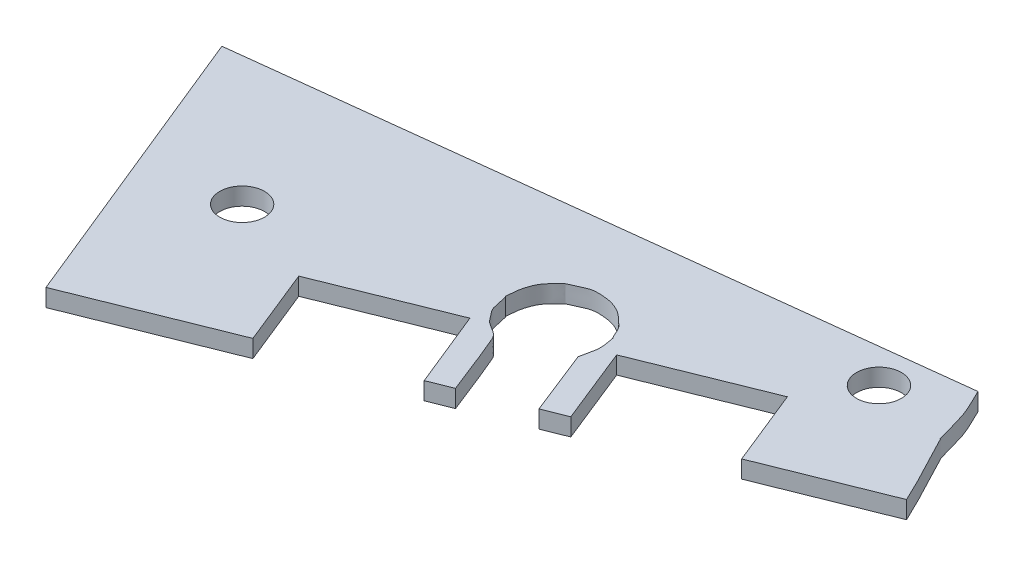
SolidWorks part; units mm, degrees
ref_plane "Front Plane" through (0, 0, 0) normal (0, 0, 1) x (1, 0, 0)
ref_plane "Top Plane" through (0, 0, 0) normal (0, 1, 0) x (1, 0, 0)
ref_plane "Right Plane" through (0, 0, 0) normal (1, 0, 0) x (0, 0, -1)
sketch "Sketch1" plane through (0, 0, 0) normal (0, 1, 0) x (1, 0, 0)
  line L0 (6.1521, 12.0078) -> (30.7603, 12.0078) construction
  line L1 (-3.9482, 25.8578) -> (34.7084, 30.3726)
  line L2 (41.3065, 14.4944) -> (26.3793, 8.5562)
  line L3 (26.3793, 8.5562) -> (21.5711, 20.6728)
  line L4 (22.9999, 7.2071) -> (6.3717, 0.5247)
  line L5 (6.3717, 0.5247) -> (-3.9482, 25.8578)
  line L6 (29.528, 24.668) -> (31.2954, 20.2924)
  line L11 (31.2954, 20.2924) -> (24.3349, 17.4974)
  line L12 (24.3349, 17.4974) -> (22.5827, 21.866)
  line L13 (22.5827, 21.866) -> (29.528, 24.668)
  line L14 (16.5778, 19.4932) -> (18.3623, 15.098)
  line L19 (18.3623, 15.098) -> (11.3765, 12.3133)
  line L20 (11.3765, 12.3133) -> (9.6115, 16.6866)
  line L21 (9.6115, 16.6866) -> (16.5778, 19.4932)
  line L22 (32.7866, 19.2988) -> (34.5598, 14.9094)
  line L23 (34.5598, 14.9094) -> (26.6479, 11.7224)
  line L24 (26.6479, 11.7224) -> (24.8826, 16.1536)
  line L25 (24.8826, 16.1536) -> (32.7866, 19.2988)
  line L26 (18.8984, 13.7726) -> (20.6613, 9.3244)
  line L27 (20.6613, 9.3244) -> (12.7599, 6.178)
  line L28 (12.7599, 6.178) -> (10.9743, 10.6019)
  line L29 (10.9743, 10.6019) -> (18.8984, 13.7726)
  circle A0 centre (31.582, 27.844) radius 1.2816
  circle A1 centre (4.4439, 18.6222) radius 1.2791
  spline S0 degree 3 poles (34.7084, 30.3726) (34.9423, 29.8626) (35.2165, 29.3692) (35.41, 28.8426) (35.6349, 28.2308) (35.7689, 27.5892) (35.9606, 26.9662) (35.9659, 26.9489) (35.9911, 26.9442) (35.9993, 26.9281) (36.7439, 25.465) (37.5642, 24.0369) (38.2178, 22.5309) (38.8653, 21.0391) (40.4414, 16.9604) (41.3065, 14.4944) knots 0 0 0 0 1 1 1 2 2 2 3 3 3 4 4 4 5 5 5 5
  spline S1 degree 3 poles (21.5711, 20.6728) (21.6349, 21.0182) (21.7486, 21.358) (21.7624, 21.7089) (21.7742, 22.0053) (21.6958, 22.2987) (21.6469, 22.5913) (21.6439, 22.6091) (21.6175, 22.614) (21.6085, 22.6296) (21.4549, 22.8982) (21.3835, 23.2349) (21.1477, 23.4352) (20.9055, 23.6408) (20.6926, 23.8883) (20.4183, 24.0487) (20.1599, 24.1998) (19.8708, 24.3154) (19.5741, 24.3552) (19.1803, 24.408) (18.7433, 24.4488) (18.3847, 24.2778) (18.1315, 24.1571) (17.8707, 24.0528) (17.6175, 23.9321) (17.6011, 23.9243) (17.5915, 23.9069) (17.5791, 23.8937) (17.3615, 23.6637) (17.1044, 23.4652) (16.9272, 23.2028) (16.7797, 22.9842) (16.6873, 22.7287) (16.6206, 22.4736) (16.5456, 22.1866) (16.5442, 21.8852) (16.506, 21.591) knots 0 0 0 0 1 1 1 2 2 2 3 3 3 4 4 4 5 5 5 6 6 6 7 7 7 8 8 8 9 9 9 10 10 10 11 11 11 12 12 12 12
  spline S2 degree 3 poles (16.506, 21.591) (16.5188, 21.5783) (16.5398, 21.5702) (16.5444, 21.5527) (16.6174, 21.2736) (16.6638, 20.9879) (16.7368, 20.7087) (16.8068, 20.441) (17.044, 20.2485) (17.1977, 20.0184) (17.4656, 19.6171) (18.0312, 19.5778) (18.2342, 19.0982) (19.1275, 16.9888) (19.3467, 16.3313) (20.0022, 14.687) (21.5189, 10.8821) (22.0115, 9.9866) (22.9999, 7.2071) knots 0 0 0 0 1 1 1 2 2 2 3 3 3 4 4 4 5 5 5 6 6 6 6
  dimension "D1" = 17.9207
extrude "Boss-Extrude1" add sketch "Sketch1" along normal blind 1.19
sketch "Sketch2" plane through (0, 0, 0) normal (0, -1, 0) x (1, 0, 0)
  line L2 (2.1219, -8.578) -> (39.6665, -23.6537)
  line L3 (39.6665, -23.6537) -> (44.4331, -11.783)
  line L4 (44.4331, -11.783) -> (5.9759, 3.6591)
  line L5 (5.9759, 3.6591) -> (2.1219, -8.578)
extrude "Cut-Extrude1" cut sketch "Sketch2" against normal blind 2.54
sketch "Sketch3" plane through (0, 0, 0) normal (0, -1, 0) x (1, 0, 0)
  line L0 (10.9345, -13.4085) -> (11.6629, -11.6037)
  line L1 (9.6115, -16.6866) -> (11.3765, -12.3133) construction
  line L2 (11.6629, -11.6037) -> (18.1781, -14.9572)
  line L3 (18.1781, -14.9572) -> (16.6989, -15.1999)
  line L4 (16.6989, -15.1999) -> (10.9345, -13.4085)
extrude "Cut-Extrude2" cut sketch "Sketch3" against normal blind 2.54
sketch "Sketch4" plane through (-2.6715, 0, -6.6532) normal (0.3726, 0, 0.928) x (0.928, 0, -0.3726)
  line L0 (6.063, 0) -> (6.063, 1.19) construction
  line L1 (15.1455, 0) -> (15.1455, 1.19) construction
  line L2 (22.6657, 1.19) -> (22.6657, 0) construction
  line L3 (29.1023, 1.19) -> (29.1023, 0) construction
  line L4 (43.8417, 1.19) -> (43.8417, 0) construction
  line L6 (43.8417, 0.19) -> (5.0686, 0.19)
  line L7 (5.0686, 0.19) -> (5.5945, -1.0415)
  line L8 (5.5945, -1.0415) -> (45.2488, -1.8615)
  line L9 (45.2488, -1.8615) -> (43.8417, 0.19)
  point P0 (6.063, 0.19)
  point P1 (15.1455, 0.19)
  point P4 (22.6657, 0.19)
  point P7 (29.1023, 0.19)
  point P10 (43.8417, 0.19)
  dimension "D1" = 1
  dimension "D2" = 1
  dimension "D3" = 1
  dimension "D4" = 1
  dimension "D5" = 1
extrude "Cut-Extrude4" cut sketch "Sketch4" against normal blind 19.812
